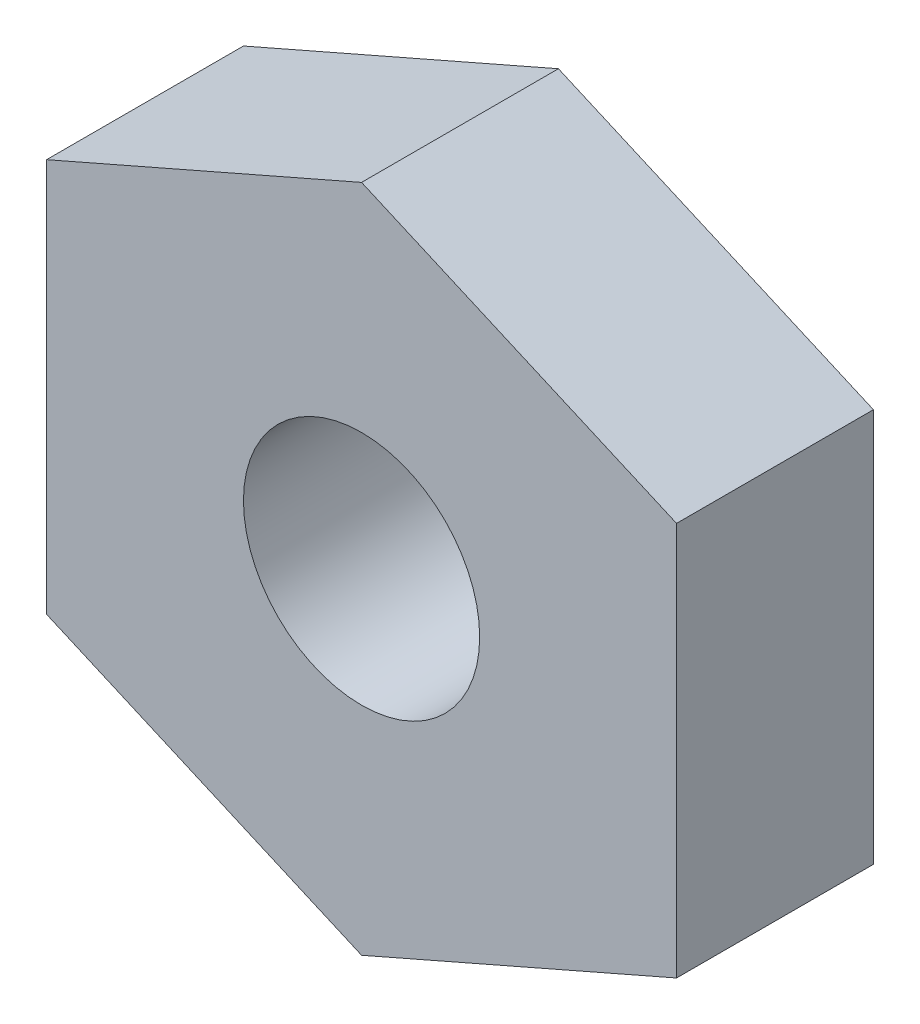
SolidWorks part; units mm, degrees
ref_plane "Alzado" through (0, 0, 0) normal (0, 0, 1) x (1, 0, 0)
ref_plane "Planta" through (0, 0, 0) normal (0, 1, 0) x (1, 0, 0)
ref_plane "Vista lateral" through (0, 0, 0) normal (1, 0, 0) x (0, 0, -1)
sketch "Croquis1" plane through (0, 0, 0) normal (0, 0, 1) x (1, 0, 0)
  line L1 (-35.0407, 0) -> (-35.0407, 2.5)
  line L2 (-35.0407, 0) -> (-35.0407, -2.5)
  line L3 (-27.0407, -2.5) -> (-27.0407, 2.5)
  line L5 (-31.0407, 4.25) -> (-35.0407, 2.5)
  line L6 (-31.0407, 4.25) -> (-27.0407, 2.5)
  line L8 (-31.0407, -4.25) -> (-35.0407, -2.5)
  line L9 (-31.0407, -4.25) -> (-27.0407, -2.5)
extrude "Saliente-Extruir1" add sketch "Croquis1" along normal blind 2.5
sketch "Croquis2" plane through (0, 0, 2.5) normal (0, 0, 1) x (1, 0, 0)
  circle A0 centre (-31.0407, 0) radius 1.5
extrude "Cortar-Extruir2" cut sketch "Croquis2" against normal blind 2.5
